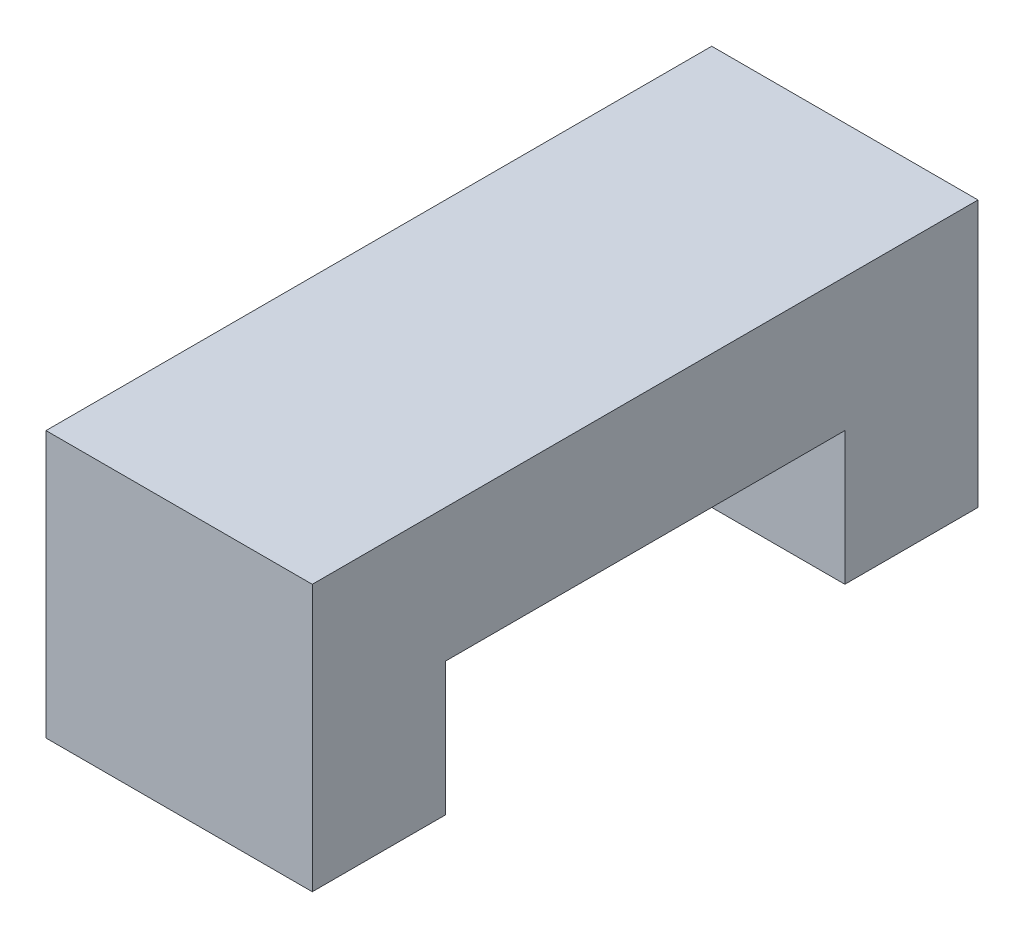
SolidWorks part; units mm, degrees
ref_plane "前视基准面" through (0, 0, 0) normal (0, 0, 1) x (1, 0, 0)
ref_plane "上视基准面" through (0, 0, 0) normal (0, 1, 0) x (1, 0, 0)
ref_plane "右视基准面" through (0, 0, 0) normal (1, 0, 0) x (0, 0, -1)
other "Configuration Table"
sketch "草图1" plane through (0, 0, 0) normal (1, 0, 0) x (0, 0, -1)
  line L0 (0, 0) -> (-5, 0)
  line L1 (-5, 0) -> (-5, 10)
  line L2 (-5, 10) -> (20, 10)
  line L3 (20, 10) -> (20, 0)
  line L4 (20, 0) -> (15, 0)
  line L5 (15, 0) -> (15, 5)
  line L6 (15, 5) -> (0, 5)
  line L7 (0, 5) -> (0, 0)
  point P3 (0, 0)
  dimension "D1" = 15
  dimension "D2" = 5
  dimension "D3" = 5
  dimension "D4" = 5
  dimension "D5" = 5
extrude "凸台-拉伸1" add sketch "草图1" along normal blind 10
